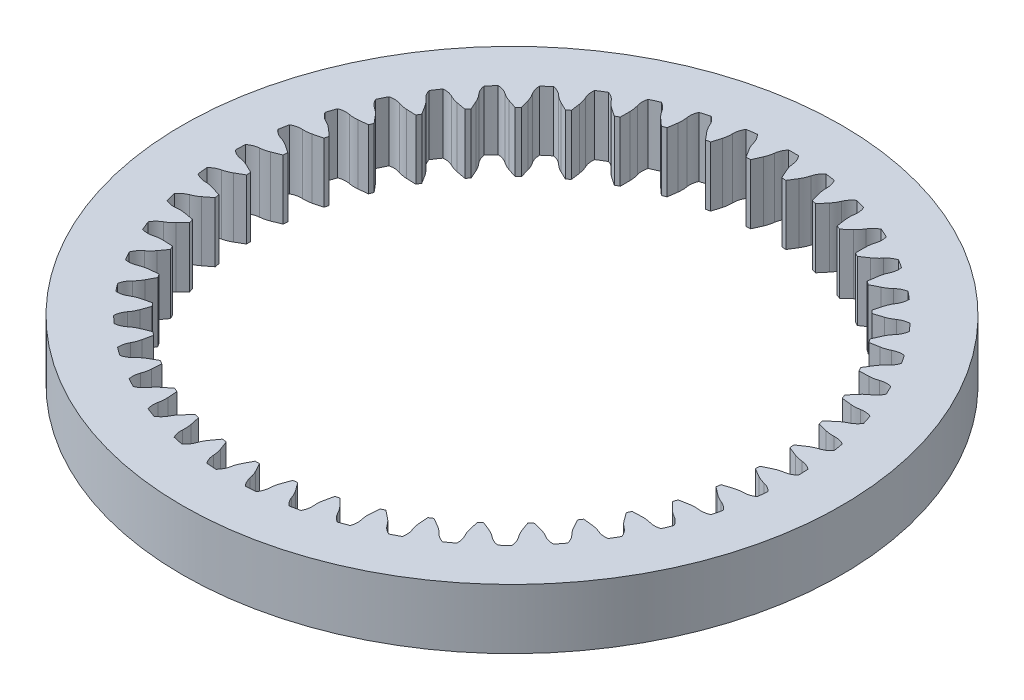
SolidWorks part; units mm, degrees
ref_plane "Alzado" through (0, 0, 0) normal (0, 0, 1) x (1, 0, 0)
ref_plane "Planta" through (0, 0, 0) normal (0, 1, 0) x (1, 0, 0)
ref_plane "Vista lateral" through (0, 0, 0) normal (1, 0, 0) x (0, 0, -1)
sketch "Croquis2" plane through (0, 0, 0) normal (0, 1, 0) x (1, 0, 0)
  circle A0 centre (0, 0) radius 42.5
  circle A1 centre (0, 0) radius 55
  dimension "D1" = 85
  dimension "D2" = 110
extrude "Saliente-Extruir1" add sketch "Croquis2" along normal blind 10
sketch "Croquis4" plane through (0, 10, 0) normal (0, 1, 0) x (1, 0, 0)
  line L0 (0, 42.5) -> (0, 76.3336) construction
  line L1 (-1.9463, 43.8911) -> (-2.6011, 42.4203)
  line L2 (1.9463, 43.8911) -> (2.6011, 42.4203)
  arc A0 (1.5485, 45.3398) -> (1.9463, 43.8911) centre (6.5141, 45.9246) ccw
  arc A1 (-1.5485, 45.3398) -> (-1.9463, 43.8911) centre (-6.5141, 45.9246) cw
  arc A2 (-0.834, 46.9926) -> (-1.5485, 45.3398) centre (1.57, 44.9726) ccw
  arc A4 (1.57, 44.9726) -> (-1.57, 44.9726) centre (0, 0) ccw construction
  arc A5 (0.834, 46.9926) -> (-0.834, 46.9926) centre (0, 0) ccw
  arc A7 (2.6011, 42.4203) -> (-2.6011, 42.4203) centre (0, 0) ccw
  arc A8 (1.5485, 45.3398) -> (0.834, 46.9926) centre (-1.57, 44.9726) ccw
  point P6 (1.5624, 44.7536)
  point P12 (-1.5624, 44.7536)
  dimension "D2" = 1.57
  dimension "D3" = 85
  dimension "D4" = 90
  dimension "D5" = 94
  dimension "D1" = 5
extrude "Cortar-Extruir2" cut sketch "Croquis4" against normal blind 10
pattern_circular "MatrizC2" count 45 over 360 about axis through (0, 0, 0) along (0, 1, 0) of "Cortar-Extruir2"
